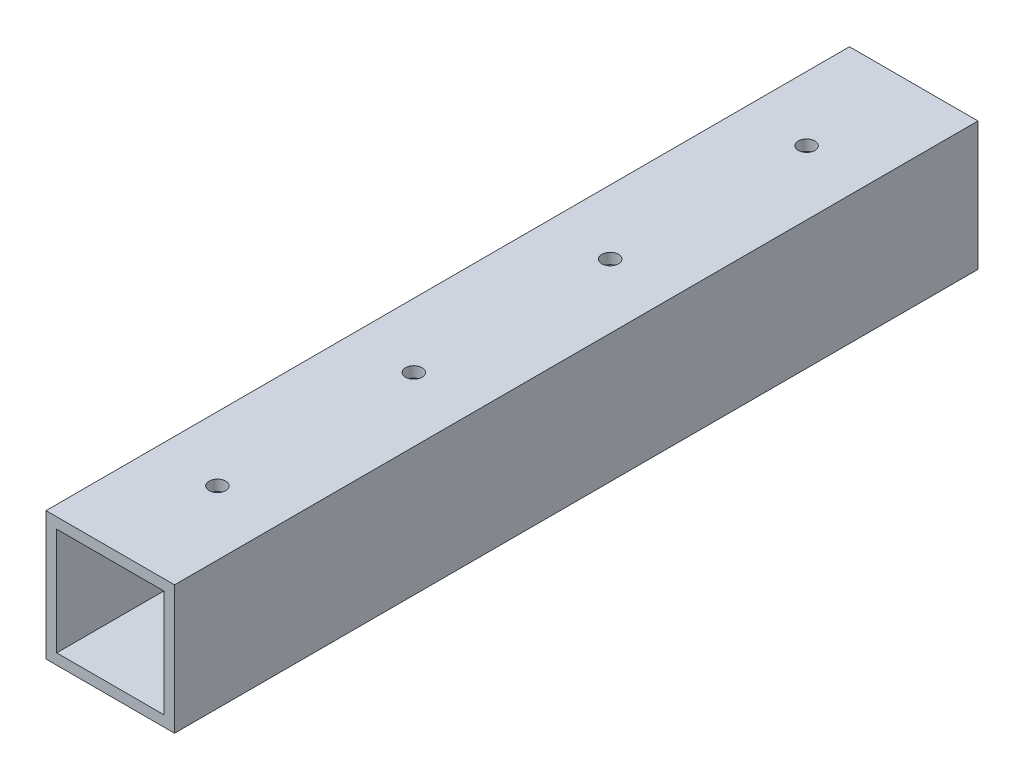
SolidWorks part; units mm, degrees
material "6061 Alloy"
ref_plane "Front Plane" through (0, 0, 0) normal (0, 0, 1) x (1, 0, 0)
ref_plane "Top Plane" through (0, 0, 0) normal (0, 1, 0) x (1, 0, 0)
ref_plane "Right Plane" through (0, 0, 0) normal (1, 0, 0) x (0, 0, -1)
sketch "Sketch1" plane through (0, 0, 0) normal (0, 0, 1) x (1, 0, 0)
  line L1 (-19.05, -19.05) -> (19.05, -19.05)
  line L2 (-19.05, -19.05) -> (-19.05, 19.05)
  line L3 (-19.05, 19.05) -> (19.05, 19.05)
  line L4 (19.05, -19.05) -> (19.05, 19.05)
  line L5 (-19.05, -19.05) -> (19.05, 19.05) construction
  line L6 (-19.05, 19.05) -> (19.05, -19.05) construction
  line L7 (-15.875, -15.875) -> (15.875, -15.875)
  line L8 (-15.875, -15.875) -> (-15.875, 15.875)
  line L9 (-15.875, 15.875) -> (15.875, 15.875)
  line L10 (15.875, -15.875) -> (15.875, 15.875)
  line L11 (-15.875, -15.875) -> (15.875, 15.875) construction
  line L12 (-15.875, 15.875) -> (15.875, -15.875) construction
  point P0 (0, 0)
  point P6 (0, 0)
  dimension "D1" = 3.175
  dimension "D2" = 3.175
  dimension "D3" = 38.1
  dimension "D4" = 38.1
extrude "Boss-Extrude1" add sketch "Sketch1" along normal blind 238.125
hole_wizard "#10 (0.1935) Diameter Hole2" positions "Sketch2" profile "Sketch3" hole size "#10" standard "ANSI Inch" end condition through all
sketch "Sketch2" plane through (0, 19.05, 0) normal (0, 1, 0) x (1, 0, 0)
  line L0 (19.05, -119.0625) -> (-19.05, -119.0625) construction
  line L1 (19.05, -238.125) -> (19.05, 0) construction
  line L2 (-19.05, -238.125) -> (-19.05, 0) construction
  line L4 (19.05, 0) -> (-19.05, 0) construction
  point P0 (0, -31.75)
  point P14 (0, -89.9583)
  point P15 (0, -148.1667)
  point P16 (0, -206.375)
  dimension "D2" = 31.75
  dimension "D1" = 4
sketch "Sketch3" plane through (0, 19.05, 31.75) normal (1, 0, 0) x (0, 0, 1)
  line L0 (0, 0) -> (0, 38.1)
  line L1 (0, 38.1) -> (2.4574, 38.1)
  line L2 (2.4574, 38.1) -> (2.4574, 0)
  line L5 (2.4574, 0) -> (0, 0)
  line L11 (0, -6.35) -> (0, 107.95) construction
  dimension "Thru Hole Dia." = 4.9149
  dimension "Thru Hole Depth" = 38.1
